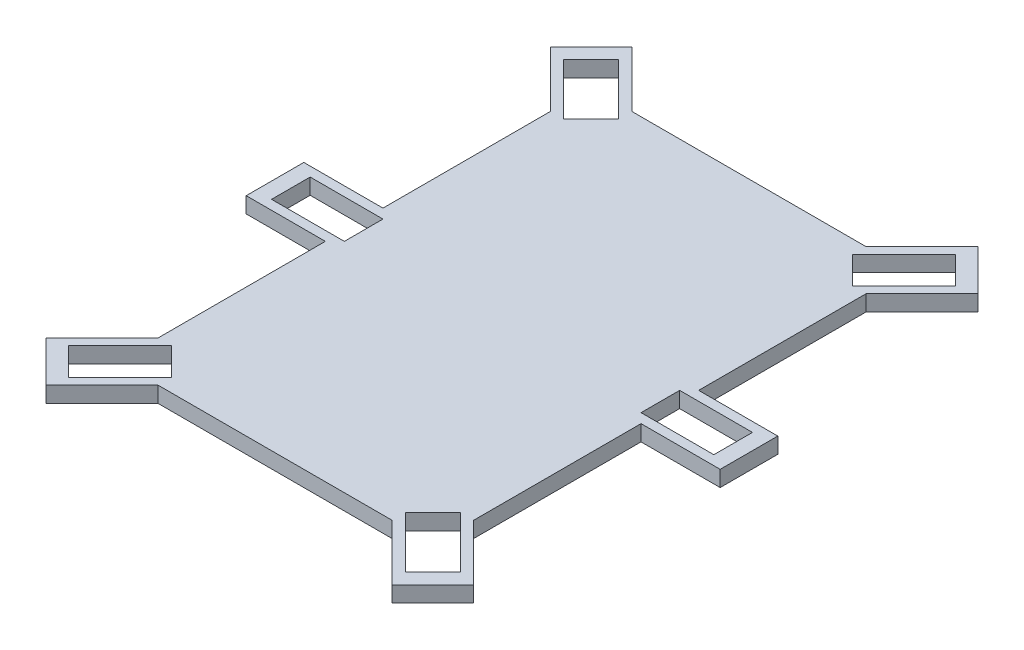
SolidWorks part; units mm, degrees
ref_plane "Front Plane" through (0, 0, 0) normal (0, 0, 1) x (1, 0, 0)
ref_plane "Top Plane" through (0, 0, 0) normal (0, 1, 0) x (1, 0, 0)
ref_plane "Right Plane" through (0, 0, 0) normal (1, 0, 0) x (0, 0, -1)
sketch "Sketch2" plane through (0, 0, 0) normal (0, 1, 0) x (1, 0, 0)
  line L0 (-192.8373, 84.9197) -> (-43.0986, 84.9197) construction
  line L9 (-117.9679, 159.7891) -> (-117.9679, 10.0504) construction
  line L54 (-154.9679, 159.7891) -> (-80.9679, 159.7891)
  line L55 (-80.9679, 159.7891) -> (-63.2902, 177.4668)
  line L56 (-63.2902, 177.4668) -> (-50.4209, 164.5974)
  line L57 (-50.4209, 164.5974) -> (-68.0986, 146.9197)
  line L58 (-68.0986, 146.9197) -> (-68.0986, 94.0197)
  line L59 (-68.0986, 94.0197) -> (-43.0986, 94.0197)
  line L60 (-43.0986, 94.0197) -> (-43.0986, 75.8197)
  line L61 (-43.0986, 75.8197) -> (-68.0986, 75.8197)
  line L62 (-68.0986, 75.8197) -> (-68.0986, 22.9197)
  line L63 (-68.0986, 22.9197) -> (-50.4209, 5.2421)
  line L64 (-50.4209, 5.2421) -> (-63.2902, -7.6273)
  line L65 (-63.2902, -7.6273) -> (-80.9679, 10.0504)
  line L66 (-80.9679, 10.0504) -> (-154.9679, 10.0504)
  line L67 (-154.9679, 10.0504) -> (-172.6456, -7.6273)
  line L68 (-172.6456, -7.6273) -> (-185.5149, 5.2421)
  line L69 (-185.5149, 5.2421) -> (-167.8373, 22.9197)
  line L70 (-167.8373, 22.9197) -> (-167.8373, 75.8197)
  line L71 (-167.8373, 75.8197) -> (-192.8373, 75.8197)
  line L72 (-192.8373, 75.8197) -> (-192.8373, 94.0197)
  line L73 (-192.8373, 94.0197) -> (-167.8373, 94.0197)
  line L74 (-167.8373, 94.0197) -> (-167.8373, 146.9197)
  line L75 (-167.8373, 146.9197) -> (-185.5149, 164.5974)
  line L76 (-185.5149, 164.5974) -> (-172.6456, 177.4668)
  line L77 (-172.6456, 177.4668) -> (-154.9679, 159.7891)
  line L78 (-171.2314, 171.8099) -> (-154.9679, 155.5464)
  line L79 (-187.8373, 91.0197) -> (-164.8373, 91.0197)
  line L80 (-187.8373, 91.0197) -> (-187.8373, 78.8197)
  line L81 (-187.8373, 78.8197) -> (-164.8373, 78.8197)
  line L82 (-164.8373, 91.0197) -> (-164.8373, 78.8197)
  line L83 (-171.2314, 171.8099) -> (-179.9417, 163.0996)
  line L84 (-154.9679, 155.5464) -> (-163.6782, 146.8362)
  line L85 (-179.9417, 163.0996) -> (-163.6782, 146.8362)
  line L86 (-80.9679, 155.5464) -> (-72.2576, 146.8362)
  line L87 (-55.9942, 163.0996) -> (-72.2576, 146.8362)
  line L88 (-64.7045, 171.8099) -> (-55.9942, 163.0996)
  line L89 (-64.7045, 171.8099) -> (-80.9679, 155.5464)
  line L90 (-64.7045, -1.9704) -> (-80.9679, 14.293)
  line L91 (-64.7045, -1.9704) -> (-55.9942, 6.7399)
  line L92 (-55.9942, 6.7399) -> (-72.2576, 23.0033)
  line L93 (-80.9679, 14.293) -> (-72.2576, 23.0033)
  line L94 (-154.9679, 14.293) -> (-163.6782, 23.0033)
  line L95 (-179.9417, 6.7399) -> (-163.6782, 23.0033)
  line L96 (-171.2314, -1.9704) -> (-179.9417, 6.7399)
  line L97 (-171.2314, -1.9704) -> (-154.9679, 14.293)
  line L98 (-48.0986, 78.8197) -> (-71.0986, 78.8197)
  line L99 (-71.0986, 91.0197) -> (-71.0986, 78.8197)
  line L100 (-48.0986, 91.0197) -> (-71.0986, 91.0197)
  line L101 (-48.0986, 91.0197) -> (-48.0986, 78.8197)
  point P7 (-154.9679, 155.5464)
  point P25 (-163.5946, 146.9197)
  point P26 (-171.2314, 171.8099)
  point P27 (-164.8373, 78.8197)
  point P28 (-187.8373, 91.0197)
  dimension "D2" = 45
  dimension "D8" = 74
  dimension "D10" = 52.9
  dimension "D11" = 18.2
  dimension "D12" = 25
extrude "Boss-Extrude1" add sketch "Sketch2" along normal blind 5
